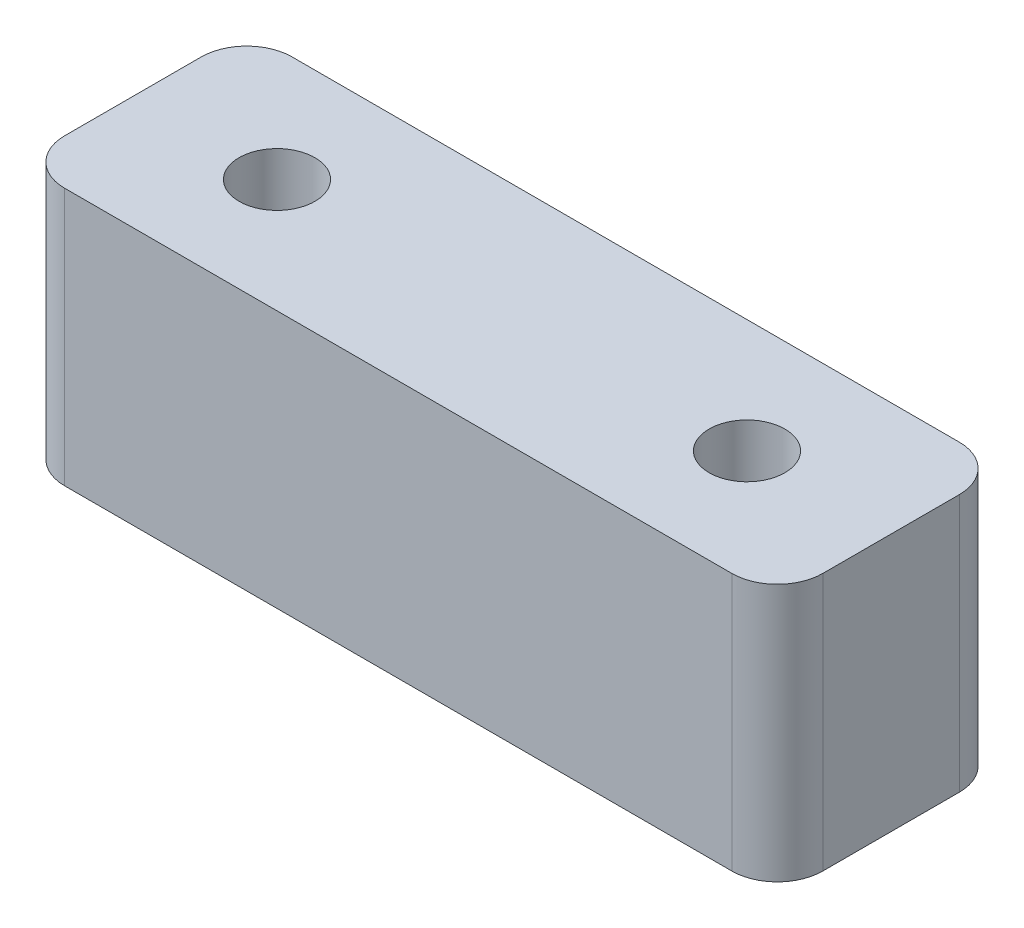
SolidWorks part; units mm, degrees
ref_plane "Front Plane" through (0, 0, 0) normal (0, 0, 1) x (1, 0, 0)
ref_plane "Top Plane" through (0, 0, 0) normal (0, 1, 0) x (1, 0, 0)
ref_plane "Right Plane" through (0, 0, 0) normal (1, 0, 0) x (0, 0, -1)
sketch "Sketch1" plane through (0, 0, 0) normal (0, 1, 0) x (1, 0, 0)
  line L1 (0, 0) -> (50, 0)
  line L2 (0, 0) -> (0, 15)
  line L3 (0, 15) -> (50, 15)
  line L4 (50, 0) -> (50, 15)
  dimension "D1" = 50
  dimension "D2" = 15
extrude "Boss-Extrude1" add sketch "Sketch1" along normal blind 17
fillet "Fillet1" radius 3 1 edges at (50, 8.5, 0)
fillet "Fillet2" radius 3 1 edges at (50, 8.5, -15)
fillet "Fillet3" radius 3 1 edges at (0, 8.5, -15)
fillet "Fillet4" radius 3 1 edges at (0, 8.5, 0)
sketch "Sketch2" plane through (0, 17, 0) normal (0, 1, 0) x (1, 0, 0)
  line L0 (50, 3) -> (50, 12) construction
  circle A0 centre (40.5, 7.5) radius 2.5
  circle A1 centre (9.5, 7.5) radius 2.5
  point P4 (50, 7.5)
  dimension "D1" = 5
  dimension "D4" = 5
  dimension "D2" = 9.5
  dimension "D3" = 31
extrude "Cut-Extrude1" cut sketch "Sketch2" against normal blind 17
